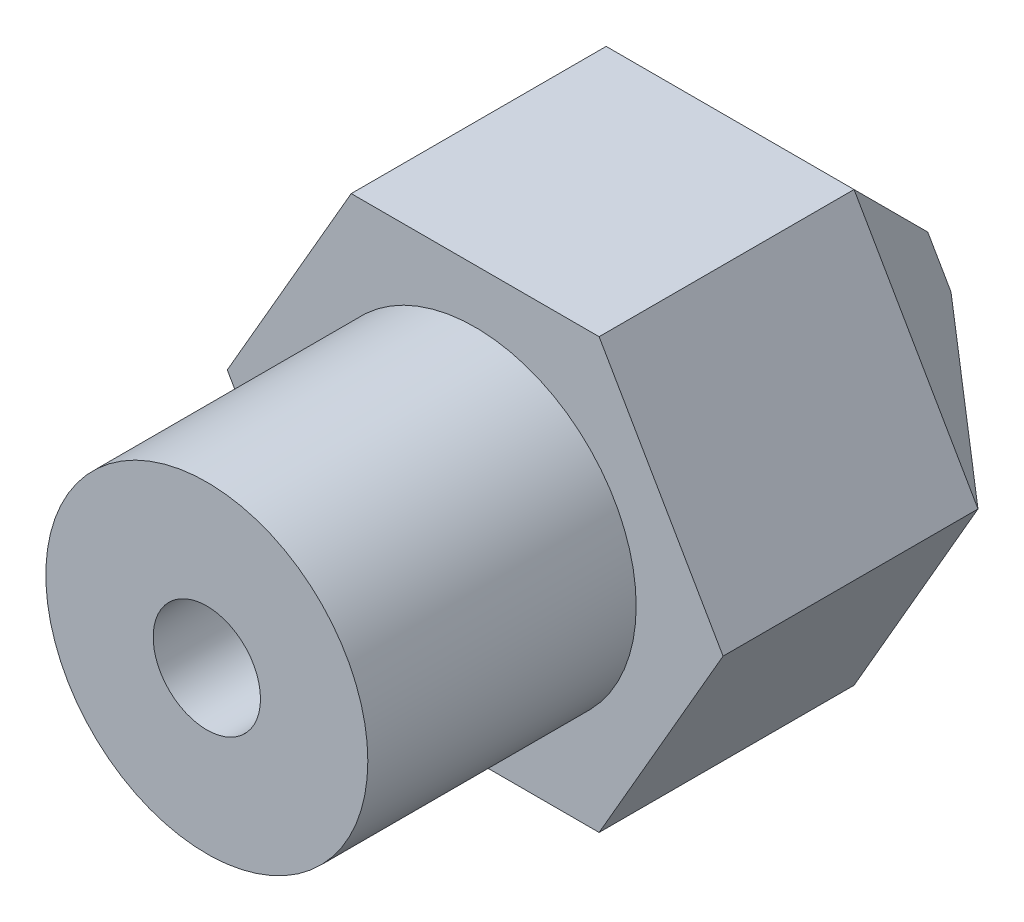
SolidWorks part; units mm, degrees
ref_plane "Plan de face" through (0, 0, 0) normal (0, 0, 1) x (1, 0, 0)
ref_plane "Plan de dessus" through (0, 0, 0) normal (0, 1, 0) x (1, 0, 0)
ref_plane "Plan de droite" through (0, 0, 0) normal (1, 0, 0) x (0, 0, -1)
sketch "Esquisse1" plane through (0, 0, 0) normal (0, 0, 1) x (1, 0, 0)
  line L1 (4.6188, 0) -> (2.3094, 4)
  line L2 (2.3094, 4) -> (-2.3094, 4)
  line L3 (-2.3094, 4) -> (-4.6188, 0)
  line L4 (-4.6188, 0) -> (-2.3094, -4)
  line L5 (-2.3094, -4) -> (2.3094, -4)
  line L6 (2.3094, -4) -> (4.6188, 0)
  circle A0 centre (0, 0) radius 4 construction
  dimension "D1" = 8
extrude "Boss.-Extru.1" add sketch "Esquisse1" along normal blind 13
sketch "Esquisse4" plane through (0, 0, 13) normal (0, 0, 1) x (1, 0, 0)
  line L1 (-5.7126, 4.5048) -> (6.4073, 4.5048)
  line L2 (-5.7126, 4.5048) -> (-5.7126, -4.3596)
  line L3 (-5.7126, -4.3596) -> (6.4073, -4.3596)
  line L4 (6.4073, 4.5048) -> (6.4073, -4.3596)
  circle A0 centre (0, 0) radius 3
extrude "Enlèv. mat.-Extru.1" cut sketch "Esquisse4" against normal blind 5
cosmetic thread "Représentation de filetage1" parameters "D1"=5, "D2"=4.891
chamfer "Chanfrein1" distance 3.25 angle 45 6 edges at (3.4641, 2, 0) (0, 4, 0) (-3.4641, 2, 0) (-3.4641, -2, 0) (0, -4, 0) (3.4641, -2, 0)
hole_wizard "Diamètre du perçage Ø1.5 (1.5)1" positions "Esquisse6" profile "Esquisse5" hole size "Ø1.5" standard "ISO"
sketch "Esquisse6" plane through (0, 0, 13) normal (0, 0, 1) x (1, 0, 0)
  point P0 (0, 0)
sketch "Esquisse5" plane through (0, 0, 13) normal (1, 0, 0) x (0, -1, 0)
  line L0 (0, 0) -> (0, 12.5506)
  line L1 (0, 12.5506) -> (0.75, 12.1)
  line L2 (0.75, 12.1) -> (0.75, 0)
  line L5 (0.75, 0) -> (0, 0)
  line L10 (0, 12.5506) -> (-0.75, 12.1) construction
  line L11 (0, -6.35) -> (0, 107.95) construction
  dimension "Diamètre du perçage" = 1.5
  dimension "Profondeur du perçage" = 12.1
  dimension "Angle de pointe" = 118
hole_wizard "Diamètre du perçage Ø2.0 (2)1" positions "Esquisse8" profile "Esquisse7" hole size "Ø2.0" standard "ISO"
sketch "Esquisse8" plane through (0, 0, 13) normal (0, 0, 1) x (1, 0, 0)
  point P0 (0, 0)
sketch "Esquisse7" plane through (0, 0, 13) normal (1, 0, 0) x (0, -1, 0)
  line L0 (0, 0) -> (0, 11.2009)
  line L1 (0, 11.2009) -> (1, 10.6)
  line L2 (1, 10.6) -> (1, 0)
  line L5 (1, 0) -> (0, 0)
  line L10 (0, 11.2009) -> (-1, 10.6) construction
  line L11 (0, -6.35) -> (0, 107.95) construction
  dimension "Diamètre du perçage" = 2
  dimension "Profondeur du perçage" = 10.6
  dimension "Angle de pointe" = 118
hole_wizard "Diamètre du perçage Ø0.4 (0.4)1" positions "Esquisse10" profile "Esquisse9" hole size "Ø0.4" standard "ISO"
sketch "Esquisse10" plane through (0, 0, 0) normal (0, 0, -1) x (-1, 0, 0)
  point P0 (0, 0)
sketch "Esquisse9" plane through (0, 0, 0) normal (1, 0, 0) x (0, 1, 0)
  line L0 (0, 0) -> (0, 1.1202)
  line L1 (0, 1.1202) -> (0.2, 1)
  line L2 (0.2, 1) -> (0.2, 0)
  line L5 (0.2, 0) -> (0, 0)
  line L10 (0, 1.1202) -> (-0.2, 1) construction
  line L11 (0, -6.35) -> (0, 107.95) construction
  dimension "Diamètre du perçage" = 0.4
  dimension "Profondeur du perçage" = 1
  dimension "Angle de pointe" = 118
